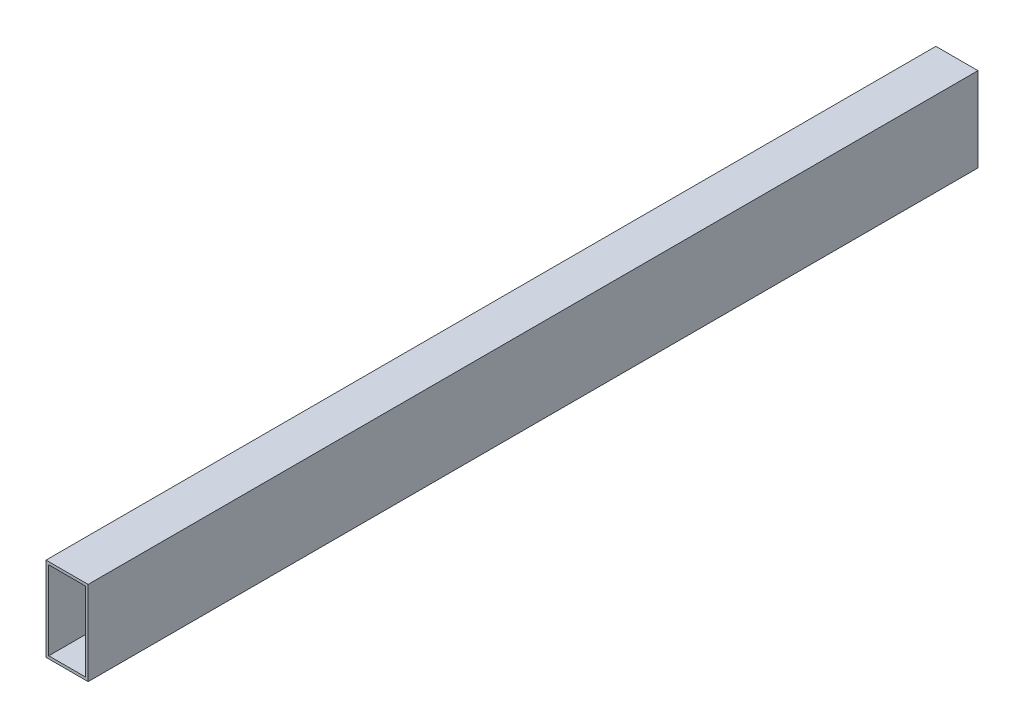
SolidWorks part; units mm, degrees
material "6061 Alloy"
ref_plane "Front Plane" through (0, 0, 0) normal (0, 0, 1) x (1, 0, 0)
ref_plane "Top Plane" through (0, 0, 0) normal (0, 1, 0) x (1, 0, 0)
ref_plane "Right Plane" through (0, 0, 0) normal (1, 0, 0) x (0, 0, -1)
sketch "Sketch1" plane through (0, 0, 0) normal (0, 0, 1) x (1, 0, 0)
  line L1 (-48.4372, -30.1994) -> (-23.0372, -30.1994)
  line L2 (-48.4372, -30.1994) -> (-48.4372, 20.6006)
  line L3 (-48.4372, 20.6006) -> (-23.0372, 20.6006)
  line L4 (-23.0372, -30.1994) -> (-23.0372, 20.6006)
  dimension "D1" = 25.4
  dimension "D2" = 50.8
extrude "Boss-Extrude1" add sketch "Sketch1" along normal blind 536.575
sketch "Sketch2" plane through (0, 0, 536.575) normal (0, 0, 1) x (1, 0, 0)
  line L0 (-48.4372, 20.6006) -> (-48.4372, -30.1994) construction
  line L1 (-46.7862, 18.9496) -> (-24.6882, 18.9496)
  line L2 (-46.7862, 18.9496) -> (-46.7862, -28.5484)
  line L3 (-46.7862, -28.5484) -> (-24.6882, -28.5484)
  line L4 (-24.6882, 18.9496) -> (-24.6882, -28.5484)
  line L5 (-46.7862, 18.9496) -> (-24.6882, -28.5484) construction
  line L6 (-46.7862, -28.5484) -> (-24.6882, 18.9496) construction
  line L7 (-23.0372, -30.1994) -> (-23.0372, 20.6006) construction
  line L8 (-23.0372, 20.6006) -> (-48.4372, 20.6006) construction
  line L9 (-48.4372, -30.1994) -> (-23.0372, -30.1994) construction
  point P0 (-35.7372, -4.7994)
  dimension "D1" = 1.651
  dimension "D2" = 1.651
  dimension "D3" = 1.651
  dimension "D4" = 1.651
extrude "Cut-Extrude1" cut sketch "Sketch2" against normal through all
